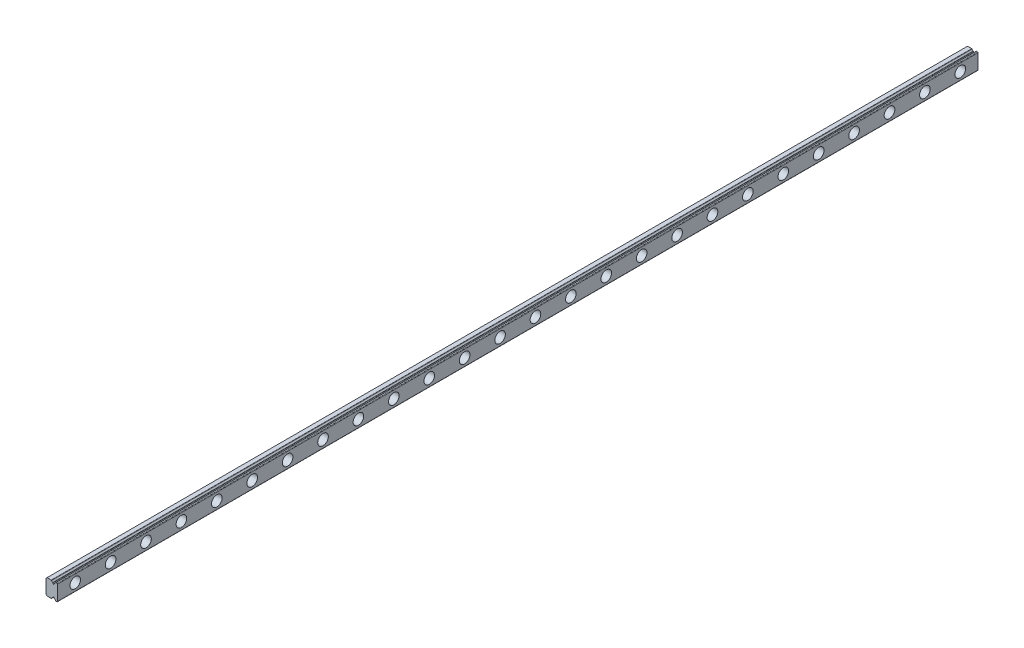
SolidWorks part; units mm, degrees
material "AISI 304"
ref_plane "前视基准面" through (0, 0, 0) normal (0, 0, 1) x (1, 0, 0)
ref_plane "上视基准面" through (0, 0, 0) normal (0, 1, 0) x (1, 0, 0)
ref_plane "右视基准面" through (0, 0, 0) normal (1, 0, 0) x (0, 0, -1)
sketch "草图1" plane through (0, 0, 0) normal (0, 0, 1) x (1, 0, 0)
  line L0 (0, 8.4) -> (0.6, 9)
  line L1 (0.6, 0) -> (2.9423, 0)
  line L2 (0, 0.6) -> (0, 8.4)
  line L3 (0.6, 9) -> (2.9423, 9)
  line L4 (6.5, 0.3) -> (6.5, 8.7)
  line L5 (0, 0.6) -> (0.6, 0)
  line L6 (4.25, 9) -> (4.25, 8) construction
  line L7 (4.25, 9) -> (4.25, 9.3) construction
  line L8 (3.85, 8) -> (3.85, 8.0351)
  line L9 (4.65, 8) -> (4.65, 8.0351)
  line L10 (5.5577, 9) -> (6.2, 9)
  line L11 (6.5, 4.5) -> (0, 4.5) construction
  line L12 (3.85, 8) -> (3.85, 8.0351)
  line L13 (4.65, 8) -> (4.65, 8.0351)
  line L14 (4.25, 0) -> (4.25, -0.3) construction
  line L15 (4.25, 0) -> (4.25, 1) construction
  line L16 (4.65, 1) -> (4.65, 0.9649)
  line L17 (3.85, 1) -> (3.85, 0.9649)
  line L18 (4.65, 1) -> (4.65, 0.9649)
  line L19 (3.85, 1) -> (3.85, 0.9649)
  line L20 (5.5577, 0) -> (6.2, 0)
  arc A0 (3.85, 8) -> (4.65, 8) centre (4.25, 8) ccw
  arc A1 (3.1291, 8.8714) -> (3.7357, 8.2158) centre (4.25, 9.3) ccw
  arc A2 (4.7643, 8.2158) -> (5.3709, 8.8714) centre (4.25, 9.3) ccw
  arc A3 (5.3709, 8.8714) -> (5.5577, 9) centre (5.5577, 8.8) cw
  arc A4 (4.65, 8.0351) -> (4.7643, 8.2158) centre (4.85, 8.0351) cw
  arc A5 (3.85, 8.0351) -> (3.7357, 8.2158) centre (3.65, 8.0351) ccw
  arc A6 (3.1291, 8.8714) -> (2.9423, 9) centre (2.9423, 8.8) ccw
  arc A7 (3.1291, 8.8714) -> (2.9423, 9) centre (2.9423, 8.8) ccw
  arc A8 (5.3709, 8.8714) -> (5.5577, 9) centre (5.5577, 8.8) cw
  arc A9 (4.65, 8.0351) -> (4.7643, 8.2158) centre (4.85, 8.0351) cw
  arc A10 (3.85, 8.0351) -> (3.7357, 8.2158) centre (3.65, 8.0351) ccw
  arc A11 (3.7357, 8.2158) -> (3.1291, 8.8714) centre (4.25, 9.3) cw
  arc A12 (5.3709, 8.8714) -> (4.7643, 8.2158) centre (4.25, 9.3) cw
  arc A13 (5.3709, 0.1286) -> (5.5577, 0) centre (5.5577, 0.2) ccw
  arc A14 (3.1291, 0.1286) -> (2.9423, 0) centre (2.9423, 0.2) cw
  arc A15 (5.3709, 0.1286) -> (4.7643, 0.7842) centre (4.25, -0.3) ccw
  arc A16 (3.7357, 0.7842) -> (3.1291, 0.1286) centre (4.25, -0.3) ccw
  arc A17 (3.85, 0.9649) -> (3.7357, 0.7842) centre (3.65, 0.9649) cw
  arc A18 (4.65, 0.9649) -> (4.7643, 0.7842) centre (4.85, 0.9649) ccw
  arc A19 (3.85, 0.9649) -> (3.7357, 0.7842) centre (3.65, 0.9649) cw
  arc A20 (4.65, 0.9649) -> (4.7643, 0.7842) centre (4.85, 0.9649) ccw
  arc A21 (4.7643, 0.7842) -> (5.3709, 0.1286) centre (4.25, -0.3) cw
  arc A22 (3.1291, 0.1286) -> (3.7357, 0.7842) centre (4.25, -0.3) cw
  arc A23 (3.85, 1) -> (4.65, 1) centre (4.25, 1) cw
  arc A24 (6.2, 0) -> (6.5, 0.3) centre (6.2, 0.3) ccw
  arc A25 (6.2, 9) -> (6.5, 8.7) centre (6.2, 8.7) cw
  point P0 (0, 0)
  point P2 (0, 9)
  point P24 (5.4119, 9)
  point P27 (4.65, 8.1686)
  point P49 (4.65, 0.8314)
  point P50 (5.4119, 0)
  point P53 (6.5, 0)
  dimension "D3" = 1
  dimension "D7" = 0.8
  dimension "D9" = 2.4
  dimension "D10" = 0.2
  dimension "D11" = 0.3
  dimension "D1" = 6.5
  dimension "D2" = 9
  dimension "D4" = 2.25
  dimension "D8" = 0.3
extrude "凸台-拉伸1" add sketch "草图1" along normal blind 400 contours A25 L10 A3 A2 A4 L9 A0 L8 A5 A1 A6 L3 L0 L2 L5 L1 A14 A16 A17 L17 A23 L16 A18 A15 A13 L20 A24 L4
sketch "草图2" plane through (6.5, 0, 0) normal (1, 0, 0) x (0, 0, -1)
  line L0 (-400, 4.5) -> (-390, 4.5) construction
  line L1 (-400, 0.3) -> (-400, 8.7) construction
  line L2 (-390, 4.5) -> (-10, 4.5) construction
  line L3 (-10, 4.5) -> (0, 4.5) construction
  line L4 (0, 0.3) -> (0, 8.7) construction
  line L5 (-10, 4.5) -> (-30, 4.5) construction
  circle A0 centre (-10, 4.5) radius 3
  circle A1 centre (-30, 4.5) radius 3
  circle A2 centre (-50, 4.5) radius 3
  circle A3 centre (-70, 4.5) radius 3
  circle A4 centre (-90, 4.5) radius 3
  circle A5 centre (-110, 4.5) radius 3
  circle A6 centre (-130, 4.5) radius 3
  circle A7 centre (-150, 4.5) radius 3
  circle A8 centre (-170, 4.5) radius 3
  circle A9 centre (-190, 4.5) radius 3
  circle A10 centre (-210, 4.5) radius 3
  circle A11 centre (-230, 4.5) radius 3
  circle A12 centre (-250, 4.5) radius 3
  circle A13 centre (-270, 4.5) radius 3
  circle A14 centre (-290, 4.5) radius 3
  circle A15 centre (-310, 4.5) radius 3
  circle A16 centre (-330, 4.5) radius 3
  circle A17 centre (-350, 4.5) radius 3
  circle A18 centre (-370, 4.5) radius 3
  circle A19 centre (-390, 4.5) radius 3
  circle A20 centre (-410, 4.5) radius 3
  circle A21 centre (-430, 4.5) radius 3
  circle A22 centre (-450, 4.5) radius 3
  circle A23 centre (-470, 4.5) radius 3
  circle A24 centre (-490, 4.5) radius 3
  circle A25 centre (-510, 4.5) radius 3
  circle A26 centre (-530, 4.5) radius 3
  circle A27 centre (-550, 4.5) radius 3
  circle A28 centre (-570, 4.5) radius 3
  circle A29 centre (-590, 4.5) radius 3
  circle A30 centre (-610, 4.5) radius 3
  circle A31 centre (-630, 4.5) radius 3
  circle A32 centre (-650, 4.5) radius 3
  circle A33 centre (-670, 4.5) radius 3
  circle A34 centre (-690, 4.5) radius 3
  circle A35 centre (-710, 4.5) radius 3
  circle A36 centre (-730, 4.5) radius 3
  circle A37 centre (-750, 4.5) radius 3
  circle A38 centre (-770, 4.5) radius 3
  circle A39 centre (-790, 4.5) radius 3
  circle A40 centre (-810, 4.5) radius 3
  circle A41 centre (-830, 4.5) radius 3
  circle A42 centre (-850, 4.5) radius 3
  circle A43 centre (-870, 4.5) radius 3
  circle A44 centre (-890, 4.5) radius 3
  circle A45 centre (-910, 4.5) radius 3
  circle A46 centre (-930, 4.5) radius 3
  circle A47 centre (-950, 4.5) radius 3
  circle A48 centre (-970, 4.5) radius 3
  circle A49 centre (-990, 4.5) radius 3
  circle A50 centre (-1010, 4.5) radius 3
  circle A51 centre (-1030, 4.5) radius 3
  circle A52 centre (-1050, 4.5) radius 3
  circle A53 centre (-1070, 4.5) radius 3
  circle A54 centre (-1090, 4.5) radius 3
  circle A55 centre (-1110, 4.5) radius 3
  circle A56 centre (-1130, 4.5) radius 3
  circle A57 centre (-1150, 4.5) radius 3
  circle A58 centre (-1170, 4.5) radius 3
  circle A59 centre (-1190, 4.5) radius 3
  circle A60 centre (-1210, 4.5) radius 3
  circle A61 centre (-1230, 4.5) radius 3
  circle A62 centre (-1250, 4.5) radius 3
  circle A63 centre (-1270, 4.5) radius 3
  circle A64 centre (-1290, 4.5) radius 3
  circle A65 centre (-1310, 4.5) radius 3
  circle A66 centre (-1330, 4.5) radius 3
  circle A67 centre (-1350, 4.5) radius 3
  circle A68 centre (-1370, 4.5) radius 3
  circle A69 centre (-1390, 4.5) radius 3
  circle A70 centre (-1410, 4.5) radius 3
  circle A71 centre (-1430, 4.5) radius 3
  circle A72 centre (-1450, 4.5) radius 3
  circle A73 centre (-1470, 4.5) radius 3
  circle A74 centre (-1490, 4.5) radius 3
  circle A75 centre (-1510, 4.5) radius 3
  circle A76 centre (-1530, 4.5) radius 3
  circle A77 centre (-1550, 4.5) radius 3
  circle A78 centre (-1570, 4.5) radius 3
  circle A79 centre (-1590, 4.5) radius 3
  circle A80 centre (-1610, 4.5) radius 3
  circle A81 centre (-1630, 4.5) radius 3
  circle A82 centre (-1650, 4.5) radius 3
  circle A83 centre (-1670, 4.5) radius 3
  circle A84 centre (-1690, 4.5) radius 3
  circle A85 centre (-1710, 4.5) radius 3
  circle A86 centre (-1730, 4.5) radius 3
  circle A87 centre (-1750, 4.5) radius 3
  circle A88 centre (-1770, 4.5) radius 3
  circle A89 centre (-1790, 4.5) radius 3
  circle A90 centre (-1810, 4.5) radius 3
  circle A91 centre (-1830, 4.5) radius 3
  circle A92 centre (-1850, 4.5) radius 3
  circle A93 centre (-1870, 4.5) radius 3
  circle A94 centre (-1890, 4.5) radius 3
  circle A95 centre (-1910, 4.5) radius 3
  circle A96 centre (-1930, 4.5) radius 3
  circle A97 centre (-1950, 4.5) radius 3
  circle A98 centre (-1970, 4.5) radius 3
  circle A99 centre (-1990, 4.5) radius 3
  circle A100 centre (-2010, 4.5) radius 3
  circle A101 centre (-2030, 4.5) radius 3
  circle A102 centre (-2050, 4.5) radius 3
  circle A103 centre (-2070, 4.5) radius 3
  circle A104 centre (-2090, 4.5) radius 3
  circle A105 centre (-2110, 4.5) radius 3
  circle A106 centre (-2130, 4.5) radius 3
  circle A107 centre (-2150, 4.5) radius 3
  circle A108 centre (-2170, 4.5) radius 3
  circle A109 centre (-2190, 4.5) radius 3
  circle A110 centre (-2210, 4.5) radius 3
  circle A111 centre (-2230, 4.5) radius 3
  circle A112 centre (-2250, 4.5) radius 3
  circle A113 centre (-2270, 4.5) radius 3
  circle A114 centre (-2290, 4.5) radius 3
  circle A115 centre (-2310, 4.5) radius 3
  circle A116 centre (-2330, 4.5) radius 3
  circle A117 centre (-2350, 4.5) radius 3
  circle A118 centre (-2370, 4.5) radius 3
  circle A119 centre (-2390, 4.5) radius 3
  circle A120 centre (-2410, 4.5) radius 3
  circle A121 centre (-2430, 4.5) radius 3
  circle A122 centre (-2450, 4.5) radius 3
  circle A123 centre (-2470, 4.5) radius 3
  dimension "D2" = 6
  dimension "D1" = 10
  dimension "D4" = 20
  dimension "D3" = 25
  dimension "D5" = 100
extrude "切除-拉伸1" cut sketch "草图2" against normal blind 4.5
sketch "草图3" plane through (2, 0, 0) normal (1, 0, 0) x (0, 0, -1)
  line L0 (-10, 4.5) -> (-30, 4.5) construction
  circle A0 centre (-10, 4.5) radius 1.75
  circle A1 centre (-30, 4.5) radius 1.75
  circle A2 centre (-50, 4.5) radius 1.75
  circle A3 centre (-70, 4.5) radius 1.75
  circle A4 centre (-90, 4.5) radius 1.75
  circle A5 centre (-110, 4.5) radius 1.75
  circle A6 centre (-130, 4.5) radius 1.75
  circle A7 centre (-150, 4.5) radius 1.75
  circle A8 centre (-170, 4.5) radius 1.75
  circle A9 centre (-190, 4.5) radius 1.75
  circle A10 centre (-210, 4.5) radius 1.75
  circle A11 centre (-230, 4.5) radius 1.75
  circle A12 centre (-250, 4.5) radius 1.75
  circle A13 centre (-270, 4.5) radius 1.75
  circle A14 centre (-290, 4.5) radius 1.75
  circle A15 centre (-310, 4.5) radius 1.75
  circle A16 centre (-330, 4.5) radius 1.75
  circle A17 centre (-350, 4.5) radius 1.75
  circle A18 centre (-370, 4.5) radius 1.75
  circle A19 centre (-390, 4.5) radius 1.75
  circle A20 centre (-410, 4.5) radius 1.75
  circle A21 centre (-430, 4.5) radius 1.75
  circle A22 centre (-450, 4.5) radius 1.75
  circle A23 centre (-470, 4.5) radius 1.75
  circle A24 centre (-490, 4.5) radius 1.75
  circle A25 centre (-510, 4.5) radius 1.75
  circle A26 centre (-530, 4.5) radius 1.75
  circle A27 centre (-550, 4.5) radius 1.75
  circle A28 centre (-570, 4.5) radius 1.75
  circle A29 centre (-590, 4.5) radius 1.75
  circle A30 centre (-610, 4.5) radius 1.75
  circle A31 centre (-630, 4.5) radius 1.75
  circle A32 centre (-650, 4.5) radius 1.75
  circle A33 centre (-670, 4.5) radius 1.75
  circle A34 centre (-690, 4.5) radius 1.75
  circle A35 centre (-710, 4.5) radius 1.75
  circle A36 centre (-730, 4.5) radius 1.75
  circle A37 centre (-750, 4.5) radius 1.75
  circle A38 centre (-770, 4.5) radius 1.75
  circle A39 centre (-790, 4.5) radius 1.75
  circle A40 centre (-810, 4.5) radius 1.75
  circle A41 centre (-830, 4.5) radius 1.75
  circle A42 centre (-850, 4.5) radius 1.75
  circle A43 centre (-870, 4.5) radius 1.75
  circle A44 centre (-890, 4.5) radius 1.75
  circle A45 centre (-910, 4.5) radius 1.75
  circle A46 centre (-930, 4.5) radius 1.75
  circle A47 centre (-950, 4.5) radius 1.75
  circle A48 centre (-970, 4.5) radius 1.75
  circle A49 centre (-990, 4.5) radius 1.75
  circle A50 centre (-1010, 4.5) radius 1.75
  circle A51 centre (-1030, 4.5) radius 1.75
  circle A52 centre (-1050, 4.5) radius 1.75
  circle A53 centre (-1070, 4.5) radius 1.75
  dimension "D1" = 3.5
  dimension "D3" = 20
  dimension "D2" = 25
  dimension "D4" = 30
extrude "切除-拉伸2" cut sketch "草图3" against normal through all
sketch "草图4" plane through (0, 0, 400) normal (0, 0, 1) x (1, 0, 0)
  line L12 (6.2, 9) -> (5.5577, 9)
  line L13 (4.65, 8.0351) -> (4.65, 8)
  line L14 (3.85, 8) -> (3.85, 8.0351)
  line L15 (2.9423, 9) -> (0.6, 9)
  line L16 (0.6, 9) -> (0, 8.4)
  line L17 (0, 8.4) -> (0, 0.6)
  line L18 (0, 0.6) -> (0.6, 0)
  line L19 (0.6, 0) -> (2.9423, 0)
  line L20 (3.85, 0.9649) -> (3.85, 1)
  line L21 (4.65, 1) -> (4.65, 0.9649)
  line L22 (5.5577, 0) -> (6.2, 0)
  line L23 (6.5, 0.3) -> (6.5, 8.7)
  line L24 (6.2, 9) -> (5.5577, 9)
  line L25 (4.65, 8.0351) -> (4.65, 8)
  line L26 (3.85, 8) -> (3.85, 8.0351)
  line L27 (2.9423, 9) -> (0.6, 9)
  line L28 (0.6, 9) -> (0, 8.4)
  line L29 (0, 8.4) -> (0, 0.6)
  line L30 (0, 0.6) -> (0.6, 0)
  line L31 (0.6, 0) -> (2.9423, 0)
  line L32 (3.85, 0.9649) -> (3.85, 1)
  line L33 (4.65, 1) -> (4.65, 0.9649)
  line L34 (5.5577, 0) -> (6.2, 0)
  line L35 (6.5, 0.3) -> (6.5, 8.7)
  arc A16 (6.5, 8.7) -> (6.2, 9) centre (6.2, 8.7) ccw
  arc A17 (5.5577, 9) -> (5.3709, 8.8714) centre (5.5577, 8.8) ccw
  arc A18 (4.7643, 8.2158) -> (5.3709, 8.8714) centre (4.25, 9.3) ccw
  arc A19 (4.7643, 8.2158) -> (4.65, 8.0351) centre (4.85, 8.0351) ccw
  arc A20 (3.85, 8) -> (4.65, 8) centre (4.25, 8) ccw
  arc A21 (3.85, 8.0351) -> (3.7357, 8.2158) centre (3.65, 8.0351) ccw
  arc A22 (3.1291, 8.8714) -> (3.7357, 8.2158) centre (4.25, 9.3) ccw
  arc A23 (3.1291, 8.8714) -> (2.9423, 9) centre (2.9423, 8.8) ccw
  arc A24 (2.9423, 0) -> (3.1291, 0.1286) centre (2.9423, 0.2) ccw
  arc A25 (3.7357, 0.7842) -> (3.1291, 0.1286) centre (4.25, -0.3) ccw
  arc A26 (3.7357, 0.7842) -> (3.85, 0.9649) centre (3.65, 0.9649) ccw
  arc A27 (4.65, 1) -> (3.85, 1) centre (4.25, 1) ccw
  arc A28 (4.65, 0.9649) -> (4.7643, 0.7842) centre (4.85, 0.9649) ccw
  arc A29 (5.3709, 0.1286) -> (4.7643, 0.7842) centre (4.25, -0.3) ccw
  arc A30 (5.3709, 0.1286) -> (5.5577, 0) centre (5.5577, 0.2) ccw
  arc A31 (6.2, 0) -> (6.5, 0.3) centre (6.2, 0.3) ccw
  arc A32 (6.5, 8.7) -> (6.2, 9) centre (6.2, 8.7) ccw
  arc A33 (5.5577, 9) -> (5.3709, 8.8714) centre (5.5577, 8.8) ccw
  arc A34 (4.7643, 8.2158) -> (5.3709, 8.8714) centre (4.25, 9.3) ccw
  arc A35 (4.7643, 8.2158) -> (4.65, 8.0351) centre (4.85, 8.0351) ccw
  arc A36 (3.85, 8) -> (4.65, 8) centre (4.25, 8) ccw
  arc A37 (3.85, 8.0351) -> (3.7357, 8.2158) centre (3.65, 8.0351) ccw
  arc A38 (3.1291, 8.8714) -> (3.7357, 8.2158) centre (4.25, 9.3) ccw
  arc A39 (3.1291, 8.8714) -> (2.9423, 9) centre (2.9423, 8.8) ccw
  arc A40 (2.9423, 0) -> (3.1291, 0.1286) centre (2.9423, 0.2) ccw
  arc A41 (3.7357, 0.7842) -> (3.1291, 0.1286) centre (4.25, -0.3) ccw
  arc A42 (3.7357, 0.7842) -> (3.85, 0.9649) centre (3.65, 0.9649) ccw
  arc A43 (4.65, 1) -> (3.85, 1) centre (4.25, 1) ccw
  arc A44 (4.65, 0.9649) -> (4.7643, 0.7842) centre (4.85, 0.9649) ccw
  arc A45 (5.3709, 0.1286) -> (4.7643, 0.7842) centre (4.25, -0.3) ccw
  arc A46 (5.3709, 0.1286) -> (5.5577, 0) centre (5.5577, 0.2) ccw
  arc A47 (6.2, 0) -> (6.5, 0.3) centre (6.2, 0.3) ccw
  dimension "D1" = 0
sketch "草图5" plane through (0, 0, 0) normal (0, 0, -1) x (-1, 0, 0)
  line L12 (-6.5, 8.7) -> (-6.5, 0.3)
  line L13 (-6.2, 0) -> (-5.5577, 0)
  line L14 (-4.65, 0.9649) -> (-4.65, 1)
  line L15 (-3.85, 1) -> (-3.85, 0.9649)
  line L16 (-2.9423, 0) -> (-0.6, 0)
  line L17 (-0.6, 0) -> (0, 0.6)
  line L18 (0, 0.6) -> (0, 8.4)
  line L19 (0, 8.4) -> (-0.6, 9)
  line L20 (-0.6, 9) -> (-2.9423, 9)
  line L21 (-3.85, 8.0351) -> (-3.85, 8)
  line L22 (-4.65, 8) -> (-4.65, 8.0351)
  line L23 (-5.5577, 9) -> (-6.2, 9)
  line L24 (-6.5, 8.7) -> (-6.5, 0.3)
  line L25 (-6.2, 0) -> (-5.5577, 0)
  line L26 (-4.65, 0.9649) -> (-4.65, 1)
  line L27 (-3.85, 1) -> (-3.85, 0.9649)
  line L28 (-2.9423, 0) -> (-0.6, 0)
  line L29 (-0.6, 0) -> (0, 0.6)
  line L30 (0, 0.6) -> (0, 8.4)
  line L31 (0, 8.4) -> (-0.6, 9)
  line L32 (-0.6, 9) -> (-2.9423, 9)
  line L33 (-3.85, 8.0351) -> (-3.85, 8)
  line L34 (-4.65, 8) -> (-4.65, 8.0351)
  line L35 (-5.5577, 9) -> (-6.2, 9)
  arc A16 (-6.2, 9) -> (-6.5, 8.7) centre (-6.2, 8.7) ccw
  arc A17 (-6.5, 0.3) -> (-6.2, 0) centre (-6.2, 0.3) ccw
  arc A18 (-5.5577, 0) -> (-5.3709, 0.1286) centre (-5.5577, 0.2) ccw
  arc A19 (-4.7643, 0.7842) -> (-5.3709, 0.1286) centre (-4.25, -0.3) ccw
  arc A20 (-4.7643, 0.7842) -> (-4.65, 0.9649) centre (-4.85, 0.9649) ccw
  arc A21 (-3.85, 1) -> (-4.65, 1) centre (-4.25, 1) ccw
  arc A22 (-3.85, 0.9649) -> (-3.7357, 0.7842) centre (-3.65, 0.9649) ccw
  arc A23 (-3.1291, 0.1286) -> (-3.7357, 0.7842) centre (-4.25, -0.3) ccw
  arc A24 (-3.1291, 0.1286) -> (-2.9423, 0) centre (-2.9423, 0.2) ccw
  arc A25 (-2.9423, 9) -> (-3.1291, 8.8714) centre (-2.9423, 8.8) ccw
  arc A26 (-3.7357, 8.2158) -> (-3.1291, 8.8714) centre (-4.25, 9.3) ccw
  arc A27 (-3.7357, 8.2158) -> (-3.85, 8.0351) centre (-3.65, 8.0351) ccw
  arc A28 (-4.65, 8) -> (-3.85, 8) centre (-4.25, 8) ccw
  arc A29 (-4.65, 8.0351) -> (-4.7643, 8.2158) centre (-4.85, 8.0351) ccw
  arc A30 (-5.3709, 8.8714) -> (-4.7643, 8.2158) centre (-4.25, 9.3) ccw
  arc A31 (-5.3709, 8.8714) -> (-5.5577, 9) centre (-5.5577, 8.8) ccw
  arc A32 (-6.2, 9) -> (-6.5, 8.7) centre (-6.2, 8.7) ccw
  arc A33 (-6.5, 0.3) -> (-6.2, 0) centre (-6.2, 0.3) ccw
  arc A34 (-5.5577, 0) -> (-5.3709, 0.1286) centre (-5.5577, 0.2) ccw
  arc A35 (-4.7643, 0.7842) -> (-5.3709, 0.1286) centre (-4.25, -0.3) ccw
  arc A36 (-4.7643, 0.7842) -> (-4.65, 0.9649) centre (-4.85, 0.9649) ccw
  arc A37 (-3.85, 1) -> (-4.65, 1) centre (-4.25, 1) ccw
  arc A38 (-3.85, 0.9649) -> (-3.7357, 0.7842) centre (-3.65, 0.9649) ccw
  arc A39 (-3.1291, 0.1286) -> (-3.7357, 0.7842) centre (-4.25, -0.3) ccw
  arc A40 (-3.1291, 0.1286) -> (-2.9423, 0) centre (-2.9423, 0.2) ccw
  arc A41 (-2.9423, 9) -> (-3.1291, 8.8714) centre (-2.9423, 8.8) ccw
  arc A42 (-3.7357, 8.2158) -> (-3.1291, 8.8714) centre (-4.25, 9.3) ccw
  arc A43 (-3.7357, 8.2158) -> (-3.85, 8.0351) centre (-3.65, 8.0351) ccw
  arc A44 (-4.65, 8) -> (-3.85, 8) centre (-4.25, 8) ccw
  arc A45 (-4.65, 8.0351) -> (-4.7643, 8.2158) centre (-4.85, 8.0351) ccw
  arc A46 (-5.3709, 8.8714) -> (-4.7643, 8.2158) centre (-4.25, 9.3) ccw
  arc A47 (-5.3709, 8.8714) -> (-5.5577, 9) centre (-5.5577, 8.8) ccw
  dimension "D1" = 0
extrude "切除-拉伸4" cut sketch "草图5" against normal blind 80
sketch "草图6" plane through (0, 0, 400) normal (0, 0, 1) x (1, 0, 0)
  line L12 (6.2, 9) -> (5.5577, 9)
  line L13 (4.65, 8.0351) -> (4.65, 8)
  line L14 (3.85, 8) -> (3.85, 8.0351)
  line L15 (2.9423, 9) -> (0.6, 9)
  line L16 (0.6, 9) -> (0, 8.4)
  line L17 (0, 8.4) -> (0, 0.6)
  line L18 (0, 0.6) -> (0.6, 0)
  line L19 (0.6, 0) -> (2.9423, 0)
  line L20 (3.85, 0.9649) -> (3.85, 1)
  line L21 (4.65, 1) -> (4.65, 0.9649)
  line L22 (5.5577, 0) -> (6.2, 0)
  line L23 (6.5, 0.3) -> (6.5, 8.7)
  line L24 (6.2, 9) -> (5.5577, 9)
  line L25 (4.65, 8.0351) -> (4.65, 8)
  line L26 (3.85, 8) -> (3.85, 8.0351)
  line L27 (2.9423, 9) -> (0.6, 9)
  line L28 (0.6, 9) -> (0, 8.4)
  line L29 (0, 8.4) -> (0, 0.6)
  line L30 (0, 0.6) -> (0.6, 0)
  line L31 (0.6, 0) -> (2.9423, 0)
  line L32 (3.85, 0.9649) -> (3.85, 1)
  line L33 (4.65, 1) -> (4.65, 0.9649)
  line L34 (5.5577, 0) -> (6.2, 0)
  line L35 (6.5, 0.3) -> (6.5, 8.7)
  arc A16 (6.5, 8.7) -> (6.2, 9) centre (6.2, 8.7) ccw
  arc A17 (5.5577, 9) -> (5.3709, 8.8714) centre (5.5577, 8.8) ccw
  arc A18 (4.7643, 8.2158) -> (5.3709, 8.8714) centre (4.25, 9.3) ccw
  arc A19 (4.7643, 8.2158) -> (4.65, 8.0351) centre (4.85, 8.0351) ccw
  arc A20 (3.85, 8) -> (4.65, 8) centre (4.25, 8) ccw
  arc A21 (3.85, 8.0351) -> (3.7357, 8.2158) centre (3.65, 8.0351) ccw
  arc A22 (3.1291, 8.8714) -> (3.7357, 8.2158) centre (4.25, 9.3) ccw
  arc A23 (3.1291, 8.8714) -> (2.9423, 9) centre (2.9423, 8.8) ccw
  arc A24 (2.9423, 0) -> (3.1291, 0.1286) centre (2.9423, 0.2) ccw
  arc A25 (3.7357, 0.7842) -> (3.1291, 0.1286) centre (4.25, -0.3) ccw
  arc A26 (3.7357, 0.7842) -> (3.85, 0.9649) centre (3.65, 0.9649) ccw
  arc A27 (4.65, 1) -> (3.85, 1) centre (4.25, 1) ccw
  arc A28 (4.65, 0.9649) -> (4.7643, 0.7842) centre (4.85, 0.9649) ccw
  arc A29 (5.3709, 0.1286) -> (4.7643, 0.7842) centre (4.25, -0.3) ccw
  arc A30 (5.3709, 0.1286) -> (5.5577, 0) centre (5.5577, 0.2) ccw
  arc A31 (6.2, 0) -> (6.5, 0.3) centre (6.2, 0.3) ccw
  arc A32 (6.5, 8.7) -> (6.2, 9) centre (6.2, 8.7) ccw
  arc A33 (5.5577, 9) -> (5.3709, 8.8714) centre (5.5577, 8.8) ccw
  arc A34 (4.7643, 8.2158) -> (5.3709, 8.8714) centre (4.25, 9.3) ccw
  arc A35 (4.7643, 8.2158) -> (4.65, 8.0351) centre (4.85, 8.0351) ccw
  arc A36 (3.85, 8) -> (4.65, 8) centre (4.25, 8) ccw
  arc A37 (3.85, 8.0351) -> (3.7357, 8.2158) centre (3.65, 8.0351) ccw
  arc A38 (3.1291, 8.8714) -> (3.7357, 8.2158) centre (4.25, 9.3) ccw
  arc A39 (3.1291, 8.8714) -> (2.9423, 9) centre (2.9423, 8.8) ccw
  arc A40 (2.9423, 0) -> (3.1291, 0.1286) centre (2.9423, 0.2) ccw
  arc A41 (3.7357, 0.7842) -> (3.1291, 0.1286) centre (4.25, -0.3) ccw
  arc A42 (3.7357, 0.7842) -> (3.85, 0.9649) centre (3.65, 0.9649) ccw
  arc A43 (4.65, 1) -> (3.85, 1) centre (4.25, 1) ccw
  arc A44 (4.65, 0.9649) -> (4.7643, 0.7842) centre (4.85, 0.9649) ccw
  arc A45 (5.3709, 0.1286) -> (4.7643, 0.7842) centre (4.25, -0.3) ccw
  arc A46 (5.3709, 0.1286) -> (5.5577, 0) centre (5.5577, 0.2) ccw
  arc A47 (6.2, 0) -> (6.5, 0.3) centre (6.2, 0.3) ccw
  dimension "D1" = 0
extrude "凸台-拉伸2" add sketch "草图6" along normal blind 200
sketch "草图7" plane through (0, 0, 0) normal (-1, 0, 0) x (0, 0, 1)
  circle A0 centre (390, 4.5) radius 1.75 construction
  circle A1 centre (390, 4.5) radius 1.75
  circle A2 centre (410, 4.5) radius 1.75
  circle A3 centre (430, 4.5) radius 1.75
  circle A4 centre (450, 4.5) radius 1.75
  circle A5 centre (470, 4.5) radius 1.75
  circle A6 centre (490, 4.5) radius 1.75
  circle A7 centre (510, 4.5) radius 1.75
  circle A8 centre (530, 4.5) radius 1.75
  circle A9 centre (550, 4.5) radius 1.75
  circle A10 centre (570, 4.5) radius 1.75
  circle A11 centre (590, 4.5) radius 1.75
  dimension "D1" = 11
extrude "切除-拉伸5" cut sketch "草图7" against normal blind 100
sketch "草图8" plane through (6.5, 0, 0) normal (1, 0, 0) x (0, 0, -1)
  circle A0 centre (-390, 4.5) radius 3 construction
  circle A1 centre (-390, 4.5) radius 3
  circle A2 centre (-410, 4.5) radius 3
  circle A3 centre (-430, 4.5) radius 3
  circle A4 centre (-450, 4.5) radius 3
  circle A5 centre (-470, 4.5) radius 3
  circle A6 centre (-490, 4.5) radius 3
  circle A7 centre (-510, 4.5) radius 3
  circle A8 centre (-530, 4.5) radius 3
  circle A9 centre (-550, 4.5) radius 3
  circle A10 centre (-570, 4.5) radius 3
  circle A11 centre (-590, 4.5) radius 3
  dimension "D1" = 11
extrude "切除-拉伸6" cut sketch "草图8" against normal blind 4.5
sketch "草图10" plane through (0, 0, 80) normal (0, 0, -1) x (-1, 0, 0)
  line L12 (-6.5, 8.7) -> (-6.5, 0.3)
  line L13 (-6.2, 0) -> (-5.5577, 0)
  line L14 (-4.65, 0.9649) -> (-4.65, 1)
  line L15 (-3.85, 1) -> (-3.85, 0.9649)
  line L16 (-2.9423, 0) -> (-0.6, 0)
  line L17 (-0.6, 0) -> (0, 0.6)
  line L18 (0, 0.6) -> (0, 8.4)
  line L19 (0, 8.4) -> (-0.6, 9)
  line L20 (-0.6, 9) -> (-2.9423, 9)
  line L21 (-3.85, 8.0351) -> (-3.85, 8)
  line L22 (-4.65, 8) -> (-4.65, 8.0351)
  line L23 (-5.5577, 9) -> (-6.2, 9)
  line L24 (-6.5, 8.7) -> (-6.5, 0.3)
  line L25 (-6.2, 0) -> (-5.5577, 0)
  line L26 (-4.65, 0.9649) -> (-4.65, 1)
  line L27 (-3.85, 1) -> (-3.85, 0.9649)
  line L28 (-2.9423, 0) -> (-0.6, 0)
  line L29 (-0.6, 0) -> (0, 0.6)
  line L30 (0, 0.6) -> (0, 8.4)
  line L31 (0, 8.4) -> (-0.6, 9)
  line L32 (-0.6, 9) -> (-2.9423, 9)
  line L33 (-3.85, 8.0351) -> (-3.85, 8)
  line L34 (-4.65, 8) -> (-4.65, 8.0351)
  line L35 (-5.5577, 9) -> (-6.2, 9)
  arc A16 (-6.2, 9) -> (-6.5, 8.7) centre (-6.2, 8.7) ccw
  arc A17 (-6.5, 0.3) -> (-6.2, 0) centre (-6.2, 0.3) ccw
  arc A18 (-5.5577, 0) -> (-5.3709, 0.1286) centre (-5.5577, 0.2) ccw
  arc A19 (-4.7643, 0.7842) -> (-5.3709, 0.1286) centre (-4.25, -0.3) ccw
  arc A20 (-4.7643, 0.7842) -> (-4.65, 0.9649) centre (-4.85, 0.9649) ccw
  arc A21 (-3.85, 1) -> (-4.65, 1) centre (-4.25, 1) ccw
  arc A22 (-3.85, 0.9649) -> (-3.7357, 0.7842) centre (-3.65, 0.9649) ccw
  arc A23 (-3.1291, 0.1286) -> (-3.7357, 0.7842) centre (-4.25, -0.3) ccw
  arc A24 (-3.1291, 0.1286) -> (-2.9423, 0) centre (-2.9423, 0.2) ccw
  arc A25 (-2.9423, 9) -> (-3.1291, 8.8714) centre (-2.9423, 8.8) ccw
  arc A26 (-3.7357, 8.2158) -> (-3.1291, 8.8714) centre (-4.25, 9.3) ccw
  arc A27 (-3.7357, 8.2158) -> (-3.85, 8.0351) centre (-3.65, 8.0351) ccw
  arc A28 (-4.65, 8) -> (-3.85, 8) centre (-4.25, 8) ccw
  arc A29 (-4.65, 8.0351) -> (-4.7643, 8.2158) centre (-4.85, 8.0351) ccw
  arc A30 (-5.3709, 8.8714) -> (-4.7643, 8.2158) centre (-4.25, 9.3) ccw
  arc A31 (-5.3709, 8.8714) -> (-5.5577, 9) centre (-5.5577, 8.8) ccw
  arc A32 (-6.2, 9) -> (-6.5, 8.7) centre (-6.2, 8.7) ccw
  arc A33 (-6.5, 0.3) -> (-6.2, 0) centre (-6.2, 0.3) ccw
  arc A34 (-5.5577, 0) -> (-5.3709, 0.1286) centre (-5.5577, 0.2) ccw
  arc A35 (-4.7643, 0.7842) -> (-5.3709, 0.1286) centre (-4.25, -0.3) ccw
  arc A36 (-4.7643, 0.7842) -> (-4.65, 0.9649) centre (-4.85, 0.9649) ccw
  arc A37 (-3.85, 1) -> (-4.65, 1) centre (-4.25, 1) ccw
  arc A38 (-3.85, 0.9649) -> (-3.7357, 0.7842) centre (-3.65, 0.9649) ccw
  arc A39 (-3.1291, 0.1286) -> (-3.7357, 0.7842) centre (-4.25, -0.3) ccw
  arc A40 (-3.1291, 0.1286) -> (-2.9423, 0) centre (-2.9423, 0.2) ccw
  arc A41 (-2.9423, 9) -> (-3.1291, 8.8714) centre (-2.9423, 8.8) ccw
  arc A42 (-3.7357, 8.2158) -> (-3.1291, 8.8714) centre (-4.25, 9.3) ccw
  arc A43 (-3.7357, 8.2158) -> (-3.85, 8.0351) centre (-3.65, 8.0351) ccw
  arc A44 (-4.65, 8) -> (-3.85, 8) centre (-4.25, 8) ccw
  arc A45 (-4.65, 8.0351) -> (-4.7643, 8.2158) centre (-4.85, 8.0351) ccw
  arc A46 (-5.3709, 8.8714) -> (-4.7643, 8.2158) centre (-4.25, 9.3) ccw
  arc A47 (-5.3709, 8.8714) -> (-5.5577, 9) centre (-5.5577, 8.8) ccw
  dimension "D1" = 0
extrude "切除-拉伸10" [suppressed] cut sketch "草图10" against normal blind 60
sketch "草图11" plane through (0, 0, 600) normal (0, 0, 1) x (1, 0, 0)
  line L12 (6.2, 9) -> (5.5577, 9)
  line L13 (4.65, 8.0351) -> (4.65, 8)
  line L14 (3.85, 8) -> (3.85, 8.0351)
  line L15 (2.9423, 9) -> (0.6, 9)
  line L16 (0.6, 9) -> (0, 8.4)
  line L17 (0, 8.4) -> (0, 0.6)
  line L18 (0, 0.6) -> (0.6, 0)
  line L19 (0.6, 0) -> (2.9423, 0)
  line L20 (3.85, 0.9649) -> (3.85, 1)
  line L21 (4.65, 1) -> (4.65, 0.9649)
  line L22 (5.5577, 0) -> (6.2, 0)
  line L23 (6.5, 0.3) -> (6.5, 8.7)
  line L24 (6.2, 9) -> (5.5577, 9)
  line L25 (4.65, 8.0351) -> (4.65, 8)
  line L26 (3.85, 8) -> (3.85, 8.0351)
  line L27 (2.9423, 9) -> (0.6, 9)
  line L28 (0.6, 9) -> (0, 8.4)
  line L29 (0, 8.4) -> (0, 0.6)
  line L30 (0, 0.6) -> (0.6, 0)
  line L31 (0.6, 0) -> (2.9423, 0)
  line L32 (3.85, 0.9649) -> (3.85, 1)
  line L33 (4.65, 1) -> (4.65, 0.9649)
  line L34 (5.5577, 0) -> (6.2, 0)
  line L35 (6.5, 0.3) -> (6.5, 8.7)
  arc A16 (6.5, 8.7) -> (6.2, 9) centre (6.2, 8.7) ccw
  arc A17 (5.5577, 9) -> (5.3709, 8.8714) centre (5.5577, 8.8) ccw
  arc A18 (4.7643, 8.2158) -> (5.3709, 8.8714) centre (4.25, 9.3) ccw
  arc A19 (4.7643, 8.2158) -> (4.65, 8.0351) centre (4.85, 8.0351) ccw
  arc A20 (3.85, 8) -> (4.65, 8) centre (4.25, 8) ccw
  arc A21 (3.85, 8.0351) -> (3.7357, 8.2158) centre (3.65, 8.0351) ccw
  arc A22 (3.1291, 8.8714) -> (3.7357, 8.2158) centre (4.25, 9.3) ccw
  arc A23 (3.1291, 8.8714) -> (2.9423, 9) centre (2.9423, 8.8) ccw
  arc A24 (2.9423, 0) -> (3.1291, 0.1286) centre (2.9423, 0.2) ccw
  arc A25 (3.7357, 0.7842) -> (3.1291, 0.1286) centre (4.25, -0.3) ccw
  arc A26 (3.7357, 0.7842) -> (3.85, 0.9649) centre (3.65, 0.9649) ccw
  arc A27 (4.65, 1) -> (3.85, 1) centre (4.25, 1) ccw
  arc A28 (4.65, 0.9649) -> (4.7643, 0.7842) centre (4.85, 0.9649) ccw
  arc A29 (5.3709, 0.1286) -> (4.7643, 0.7842) centre (4.25, -0.3) ccw
  arc A30 (5.3709, 0.1286) -> (5.5577, 0) centre (5.5577, 0.2) ccw
  arc A31 (6.2, 0) -> (6.5, 0.3) centre (6.2, 0.3) ccw
  arc A32 (6.5, 8.7) -> (6.2, 9) centre (6.2, 8.7) ccw
  arc A33 (5.5577, 9) -> (5.3709, 8.8714) centre (5.5577, 8.8) ccw
  arc A34 (4.7643, 8.2158) -> (5.3709, 8.8714) centre (4.25, 9.3) ccw
  arc A35 (4.7643, 8.2158) -> (4.65, 8.0351) centre (4.85, 8.0351) ccw
  arc A36 (3.85, 8) -> (4.65, 8) centre (4.25, 8) ccw
  arc A37 (3.85, 8.0351) -> (3.7357, 8.2158) centre (3.65, 8.0351) ccw
  arc A38 (3.1291, 8.8714) -> (3.7357, 8.2158) centre (4.25, 9.3) ccw
  arc A39 (3.1291, 8.8714) -> (2.9423, 9) centre (2.9423, 8.8) ccw
  arc A40 (2.9423, 0) -> (3.1291, 0.1286) centre (2.9423, 0.2) ccw
  arc A41 (3.7357, 0.7842) -> (3.1291, 0.1286) centre (4.25, -0.3) ccw
  arc A42 (3.7357, 0.7842) -> (3.85, 0.9649) centre (3.65, 0.9649) ccw
  arc A43 (4.65, 1) -> (3.85, 1) centre (4.25, 1) ccw
  arc A44 (4.65, 0.9649) -> (4.7643, 0.7842) centre (4.85, 0.9649) ccw
  arc A45 (5.3709, 0.1286) -> (4.7643, 0.7842) centre (4.25, -0.3) ccw
  arc A46 (5.3709, 0.1286) -> (5.5577, 0) centre (5.5577, 0.2) ccw
  arc A47 (6.2, 0) -> (6.5, 0.3) centre (6.2, 0.3) ccw
  dimension "D1" = 0
extrude "切除-拉伸11" [suppressed] cut sketch "草图11" against normal blind 60
